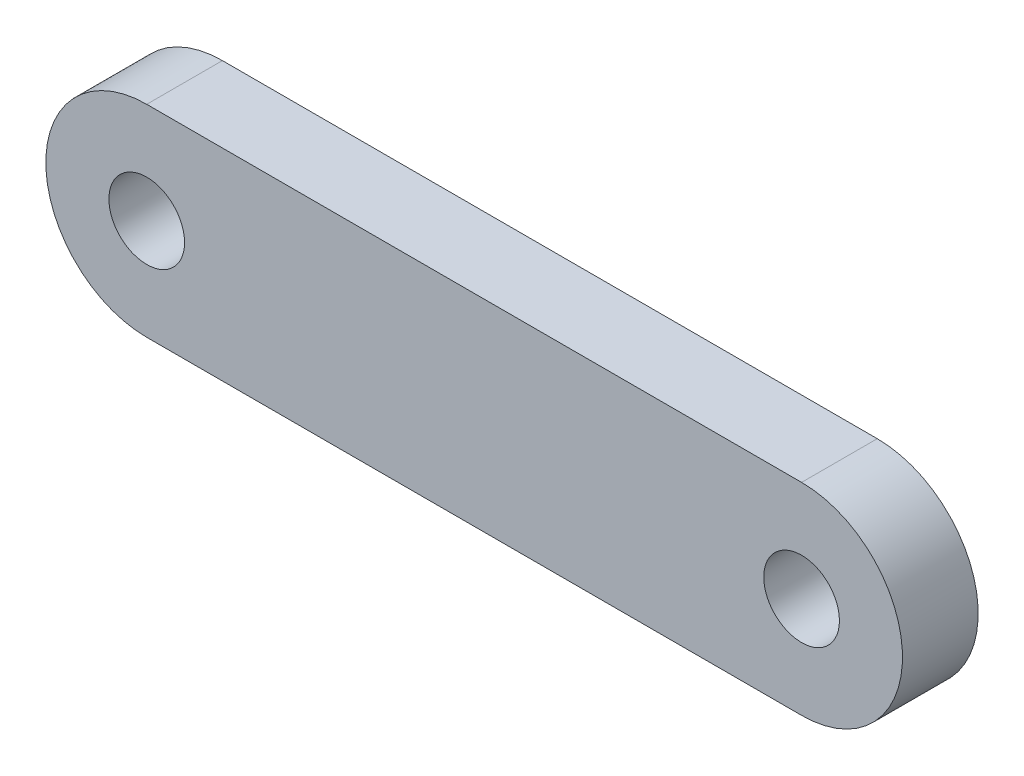
SolidWorks part; units mm, degrees
ref_plane "Front Plane" through (0, 0, 0) normal (0, 0, 1) x (1, 0, 0)
ref_plane "Top Plane" through (0, 0, 0) normal (0, 1, 0) x (1, 0, 0)
ref_plane "Right Plane" through (0, 0, 0) normal (1, 0, 0) x (0, 0, -1)
sketch "Sketch1" plane through (0, 0, 0) normal (0, 0, 1) x (1, 0, 0)
  line L0 (-23.3034, 0) -> (12.6332, 0) construction
  line L1 (-25.96, 4) -> (0, 4)
  line L2 (-25.96, -4) -> (0, -4)
  circle A0 centre (0, 0) radius 1.5
  circle A1 centre (-25.96, 0) radius 1.5
  arc A2 (-25.96, 4) -> (-25.96, -4) centre (-25.96, 0) ccw
  arc A3 (0, -4) -> (0, 4) centre (0, 0) ccw
  dimension "D1" = 3
  dimension "D2" = 3
  dimension "D4" = 8
  dimension "D5" = 8
  dimension "D3" = 25.96
extrude "Boss-Extrude1" add sketch "Sketch1" along normal blind 3
